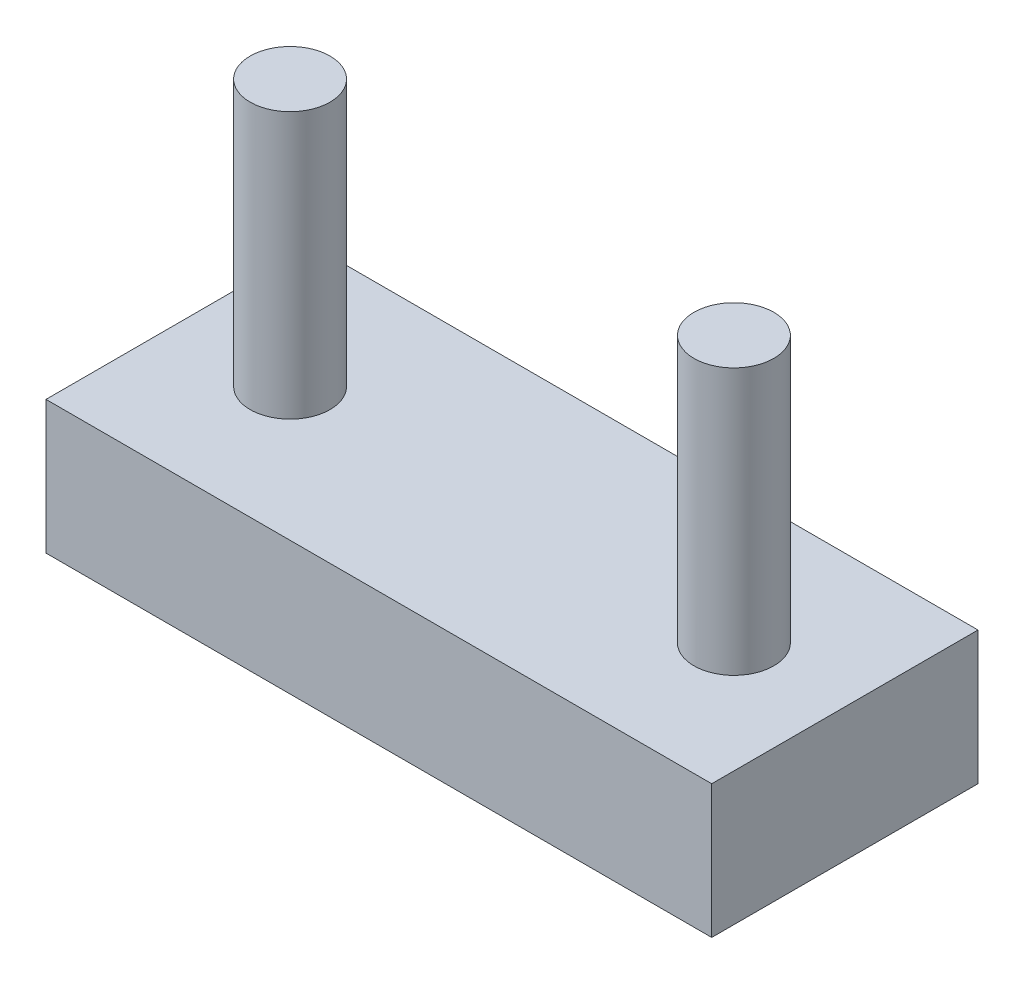
SolidWorks part; units mm, degrees
ref_plane "Alzado" through (0, 0, 0) normal (0, 0, 1) x (1, 0, 0)
ref_plane "Planta" through (0, 0, 0) normal (0, 1, 0) x (1, 0, 0)
ref_plane "Vista lateral" through (0, 0, 0) normal (1, 0, 0) x (0, 0, -1)
sketch "Croquis1" plane through (0, 0, 0) normal (0, 1, 0) x (1, 0, 0)
  line L0 (4.1665, 5) -> (20.8335, 5) construction
  line L1 (0, 0) -> (25, 0)
  line L2 (0, 0) -> (0, 10)
  line L3 (0, 10) -> (25, 10)
  line L4 (25, 0) -> (25, 10)
  point P7 (12.5, 5)
  point P8 (12.5, 0)
  point P9 (25, 5)
  dimension "D1" = 16.667
  dimension "D2" = 10
  dimension "D3" = 25
extrude "Saliente-Extruir1" add sketch "Croquis1" along normal blind 5
sketch "Croquis2" plane through (0, 5, 0) normal (0, 1, 0) x (1, 0, 0)
  circle A0 centre (4.1665, 5) radius 1.5
  circle A1 centre (20.8335, 5) radius 1.5
  dimension "D1" = 3
extrude "Saliente-Extruir2" add sketch "Croquis2" along normal blind 10
